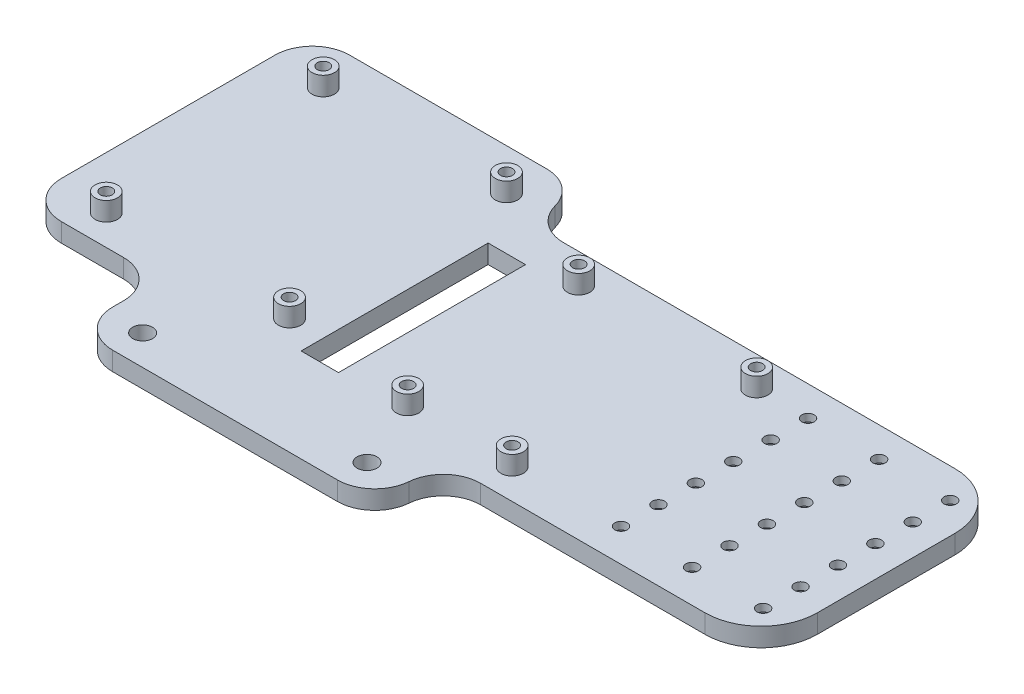
SolidWorks part; units mm, degrees
ref_plane "Front Plane" through (0, 0, 0) normal (0, 0, 1) x (1, 0, 0)
ref_plane "Top Plane" through (0, 0, 0) normal (0, 1, 0) x (1, 0, 0)
ref_plane "Right Plane" through (0, 0, 0) normal (1, 0, 0) x (0, 0, -1)
sketch "Sketch1" plane through (0, 0, 0) normal (0, 1, 0) x (1, 0, 0)
  line L1 (0, 0) -> (270, 0)
  line L2 (0, 0) -> (0, 100)
  line L3 (0, 100) -> (270, 100)
  line L4 (270, 0) -> (270, 100)
  dimension "D1" = 270
  dimension "D2" = 100
extrude "Boss-Extrude1" add sketch "Sketch1" along normal blind 5
sketch "Sketch2" plane through (0, 5, 0) normal (0, 1, 0) x (1, 0, 0)
  line L0 (150.83, 92.803) -> (204.83, 92.803)
  line L1 (10.5038, 92.4135) -> (66.5038, 92.4135)
  line L2 (10.5038, 92.4135) -> (10.5038, 7.4135)
  line L3 (10.5038, 7.4135) -> (66.5038, 7.4135)
  line L4 (66.5038, 92.4135) -> (66.5038, 7.4135)
  line L5 (90.8313, 92.4135) -> (144.8313, 92.4135)
  line L6 (90.8313, 92.4135) -> (90.8313, 23.9135)
  line L7 (90.8313, 23.9135) -> (144.8313, 23.9135)
  line L8 (144.8313, 92.4135) -> (144.8313, 23.9135)
  line L9 (150.83, 92.803) -> (150.83, 24.303)
  line L10 (150.83, 24.303) -> (204.83, 24.303)
  line L11 (204.83, 92.803) -> (204.83, 24.303)
  line L12 (210.8288, 93.1925) -> (264.8288, 93.1925)
  line L13 (210.8288, 93.1925) -> (210.8288, 24.6925)
  line L14 (210.8288, 24.6925) -> (264.8288, 24.6925)
  line L15 (264.8288, 93.1925) -> (264.8288, 24.6925)
  dimension "D1" = 85
  dimension "D2" = 56
  dimension "D3" = 54
  dimension "D4" = 68.5
  dimension "D5" = 3
sketch "Sketch3" plane through (0, 5, 0) normal (0, 1, 0) x (1, 0, 0)
  line L0 (14.0038, 88.9135) -> (63.0038, 88.9135)
  line L1 (14.0038, 88.9135) -> (14.0038, 30.9135)
  line L2 (10.5038, 92.4135) -> (66.5038, 92.4135) construction
  line L3 (10.5038, 92.4135) -> (10.5038, 7.4135) construction
  circle A0 centre (14.0038, 88.9135) radius 1.6
  circle A1 centre (63.0038, 88.9135) radius 1.6
  circle A2 centre (63.0038, 30.9135) radius 1.6
  circle A3 centre (14.0038, 30.9135) radius 1.6
  circle A4 centre (14.0038, 88.9135) radius 3
  circle A5 centre (63.0038, 88.9135) radius 3
  circle A6 centre (63.0038, 30.9135) radius 3
  circle A7 centre (14.0038, 30.9135) radius 3
  dimension "D1" = 3.2
  dimension "D2" = 6
  dimension "D3" = 49
  dimension "D4" = 49
  dimension "D5" = 58
  dimension "D6" = 58
  dimension "D7" = 3.5
  dimension "D8" = 3.5
extrude "Boss-Extrude2" add sketch "Sketch3" along normal blind 5
sketch "Sketch4" plane through (0, 5, 0) normal (0, 1, 0) x (1, 0, 0)
  circle A0 centre (14.0038, 88.9135) radius 1.6
  circle A1 centre (63.0038, 88.9135) radius 1.6
  circle A2 centre (63.0038, 30.9135) radius 1.6
  circle A3 centre (14.0038, 30.9135) radius 1.6
  dimension "D1" = 3.2
  dimension "D2" = 3.2
  dimension "D3" = 3.2
  dimension "D4" = 3.2
extrude "Cut-Extrude1" cut sketch "Sketch4" against normal blind 5
sketch "Sketch5" plane through (0, 0, 0) normal (0, -1, 0) x (-1, 0, 0)
  circle A0 centre (-63.0038, 88.9135) radius 3.25
  circle A1 centre (-14.0038, 88.9135) radius 3.25
  circle A2 centre (-14.0038, 30.9135) radius 3.25
  circle A3 centre (-63.0038, 30.9135) radius 3.25
  dimension "D1" = 6.5
  dimension "D2" = 2
  dimension "D3" = 2
extrude "Cut-Extrude2" cut sketch "Sketch5" against normal blind 3.2
sketch "Sketch6" plane through (0, 5, 0) normal (0, 1, 0) x (1, 0, 0)
  line L0 (94.0313, 77.1735) -> (141.6313, 77.1735)
  line L1 (90.8313, 92.4135) -> (144.8313, 92.4135) construction
  line L2 (144.8313, 92.4135) -> (144.8313, 23.9135) construction
  line L3 (90.8313, 92.4135) -> (90.8313, 23.9135) construction
  circle A0 centre (99.1113, 26.3735) radius 1.6
  circle A1 centre (127.0513, 26.3735) radius 1.6
  circle A2 centre (94.0313, 77.1735) radius 1.6
  circle A3 centre (141.6313, 77.1735) radius 1.6
  circle A4 centre (154.0313, 77.1735) radius 1.6
  circle A5 centre (159.1113, 26.3735) radius 1.6
  circle A6 centre (187.0513, 26.3735) radius 1.6
  circle A7 centre (201.6313, 77.1735) radius 1.6
  circle A8 centre (214.0313, 77.1735) radius 1.6
  circle A9 centre (219.1113, 26.3735) radius 1.6
  circle A10 centre (247.0513, 26.3735) radius 1.6
  circle A11 centre (261.6313, 77.1735) radius 1.6
  dimension "D1" = 3.2
  dimension "D2" = 15.24
  dimension "D3" = 50.8
  dimension "D4" = 50.8
  dimension "D5" = 17.78
  dimension "D6" = 66.04
  dimension "D7" = 45.72
  dimension "D8" = 66.04
  dimension "D9" = 3
extrude "Cut-Extrude3" cut sketch "Sketch6" against normal blind 23.2
sketch "Sketch7" plane through (0, 5, 0) normal (0, 1, 0) x (1, 0, 0)
  circle A0 centre (94.0313, 77.1735) radius 3
  circle A1 centre (141.6313, 77.1735) radius 3
  circle A2 centre (127.0513, 26.3735) radius 3
  circle A3 centre (99.1113, 26.3735) radius 3
  circle A4 centre (94.0313, 77.1735) radius 1.6
  circle A5 centre (141.6313, 77.1735) radius 1.6
  circle A6 centre (127.0513, 26.3735) radius 1.6
  circle A7 centre (99.1113, 26.3735) radius 1.6
  dimension "D1" = 6
extrude "Boss-Extrude3" add sketch "Sketch7" along normal blind 5
sketch "Sketch8" plane through (0, 0, 0) normal (0, -1, 0) x (1, 0, 0)
  circle A0 centre (94.0313, -77.1735) radius 3.25
  circle A1 centre (99.1113, -26.3735) radius 3.25
  circle A2 centre (127.0513, -26.3735) radius 3.25
  circle A3 centre (141.6313, -77.1735) radius 3.25
  dimension "D1" = 6.5
extrude "Cut-Extrude4" cut sketch "Sketch8" against normal blind 3.2
pattern_linear "LPattern1" count 3 spacing 60 along (1, 0, 0) of "Cut-Extrude4", "Boss-Extrude3"
sketch "Sketch9" plane through (0, 5, 0) normal (0, 1, 0) x (1, 0, 0)
  line L0 (0, 0) -> (270, 0) construction
  line L1 (72, 75) -> (82, 75)
  line L2 (72, 75) -> (72, 25)
  line L3 (72, 25) -> (82, 25)
  line L4 (82, 75) -> (82, 25)
  line L5 (0, 100) -> (0, 0) construction
  dimension "D1" = 10
  dimension "D2" = 50
  dimension "D3" = 25
  dimension "D4" = 72
extrude "Cut-Extrude5" cut sketch "Sketch9" against normal blind 13.2
sketch "Sketch11" plane through (0, 5, 0) normal (0, 1, 0) x (1, 0, 0)
  line L0 (270, 100) -> (0, 100) construction
  line L1 (146.6313, 100) -> (270, 100)
  line L2 (146.6313, 100) -> (146.6313, 0)
  line L3 (146.6313, 0) -> (270, 0)
  line L4 (270, 100) -> (270, 0)
  circle A0 centre (141.6313, 77.1735) radius 1.6 construction
  dimension "D1" = 5
extrude "Cut-Extrude7" cut sketch "Sketch11" against normal blind 10
sketch "Sketch12" plane through (0, 5, 0) normal (0, 1, 0) x (1, 0, 0)
  line L0 (0, 0) -> (146.6313, 0) construction
  line L1 (146.6313, 100) -> (146.6313, 0) construction
  circle A0 centre (46.6313, 8) radius 2.65
  circle A1 centre (106.6313, 8) radius 2.65
  point P4 (0, 0)
  dimension "D1" = 5.3
  dimension "D2" = 5.3
  dimension "D3" = 8
  dimension "D4" = 8
  dimension "D5" = 60
  dimension "D6" = 40
extrude "Cut-Extrude8" cut sketch "Sketch12" against normal blind 10
sketch "Sketch13" plane through (0, 5, 0) normal (0, 1, 0) x (1, 0, 0)
  line L0 (141.6313, 85.1735) -> (82, 85.1735)
  line L1 (146.6313, 100) -> (146.6313, 0) construction
  line L2 (72, 95.1735) -> (72, 100)
  line L3 (146.6313, 100) -> (0, 100) construction
  line L4 (72, 75) -> (72, 25) construction
  line L5 (116.6313, 0) -> (116.6313, 8.3735)
  line L6 (0, 0) -> (146.6313, 0) construction
  line L7 (126.6313, 18.3735) -> (136.6313, 18.3735)
  line L8 (36.6313, 0) -> (36.6313, 12.9135)
  line L9 (26.6313, 22.9135) -> (10, 22.9135)
  line L10 (0, 100) -> (0, 0) construction
  line L11 (146.6313, 28.3735) -> (146.6313, 80.1735)
  line L12 (36.6313, 0) -> (116.6313, 0)
  line L13 (0, 32.9135) -> (0, 90)
  line L14 (10, 100) -> (72, 100)
  circle A0 centre (94.0313, 77.1735) radius 1.6 construction
  circle A1 centre (106.6313, 8) radius 2.65 construction
  circle A2 centre (127.0513, 26.3735) radius 3 construction
  circle A3 centre (46.6313, 8) radius 2.65 construction
  circle A4 centre (14.0038, 30.9135) radius 3 construction
  arc A5 (82, 85.1735) -> (72, 95.1735) centre (82, 95.1735) cw
  arc A6 (116.6313, 8.3735) -> (126.6313, 18.3735) centre (126.6313, 8.3735) cw
  arc A7 (36.6313, 12.9135) -> (26.6313, 22.9135) centre (26.6313, 12.9135) ccw
  arc A8 (136.6313, 18.3735) -> (146.6313, 28.3735) centre (136.6313, 28.3735) ccw
  arc A9 (10, 22.9135) -> (0, 32.9135) centre (10, 32.9135) cw
  arc A10 (141.6313, 85.1735) -> (146.6313, 80.1735) centre (141.6313, 80.1735) cw
  arc A11 (0, 90) -> (10, 100) centre (10, 90) cw
  point P39 (146.6313, 18.3735)
  point P42 (0, 22.9135)
  point P45 (146.6313, 85.1735)
  point P48 (0, 100)
  line M30 (0, 0) -> (146.6313, 0)
  line M31 (146.6313, 0) -> (146.6313, 100)
  line M32 (146.6313, 100) -> (0, 100)
  line M33 (0, 100) -> (0, 0)
  dimension "D7" = 10
  dimension "D8" = 10
  dimension "D9" = 5
  dimension "D10" = 10
  dimension "D1" = 0
  dimension "D2" = 8
  dimension "D3" = 10
  dimension "D4" = 8
  dimension "D5" = 10
  dimension "D6" = 8
extrude "Cut-Extrude9" cut sketch "Sketch13" against normal blind 10 contours L9 A9 L8 A7 M33 M30 | L0 A10 L2 A5 M31 M32 | A8 L7 A6 L5 M30 M31
fillet "Fillet1" radius 10 3 edges at (36.6313, 2.5, 0) (116.6313, 2.5, 0) (72, 2.5, -100)
fillet "Fillet2" radius 10 1 edges at (0, 2.5, -100)
sketch "Sketch14" plane through (0, 5, 0) normal (0, 1, 0) x (1, 0, 0)
  line L1 (141.6313, 85.1735) -> (211.6313, 85.1735)
  line L2 (141.6313, 85.1735) -> (141.6313, 18.3735)
  line L3 (141.6313, 18.3735) -> (211.6313, 18.3735)
  line L4 (211.6313, 85.1735) -> (211.6313, 18.3735)
  line L5 (126.6313, 18.3735) -> (136.6313, 18.3735) construction
  line L6 (141.6313, 18.3735) -> (136.6313, 18.3735)
  line L7 (136.6313, 18.3735) -> (136.6313, 27.2758)
  line L8 (136.6313, 27.2758) -> (141.6313, 27.2758)
  line L9 (141.6313, 27.2758) -> (141.6313, 18.3735)
  point P7 (139.1313, 27.2758)
  arc M33 (136.6313, 18.3735) -> (146.6313, 28.3735) centre (136.6313, 28.3735) ccw
  line M34 (146.6313, 28.3735) -> (146.6313, 80.1735)
  arc M35 (146.6313, 80.1735) -> (141.6313, 85.1735) centre (141.6313, 80.1735) ccw
  dimension "D1" = 70
  dimension "D2" = 0
  dimension "D3" = 5
  dimension "D4" = 8.9023
  dimension "D5" = 8.9023
extrude "Boss-Extrude4" add sketch "Sketch14" against normal up to surface (5 mm away) contours L4 L1 L2 L3 M35 M34 M33 | L8 L7 L2 M33 up to face at (72.4461, 0, -44.8907)
sketch "Sketch15" plane through (0, 5, 0) normal (0, 1, 0) x (1, 0, 0)
  line L0 (141.6313, 18.3735) -> (136.6313, 18.3735)
  line L1 (136.6313, 18.3735) -> (136.6313, 19.9644)
  line L2 (136.6313, 19.9644) -> (141.6313, 19.9644)
  line L3 (141.6313, 19.9644) -> (141.6313, 18.3735)
extrude "Boss-Extrude5" add sketch "Sketch15" against normal up to surface (5 mm away) up to face at (82.7706, 0, -39.8238)
hole_wizard "Ø3.0mm Dowel Hole2" positions "3DSketch1" profile "Sketch18" hole size "Ø3.0" standard "ANSI Metric" end condition through all
sketch3d "3DSketch1"
  line L0 (211.6313, 5, -85.1735) -> (82, 5, -85.1735) construction
  point P0 (155.3664, 5, -77.1735)
  dimension "D1" = 8
sketch "Sketch18" plane through (155.3664, 5, -77.1735) normal (1, 0, 0) x (0, 0, 1)
  line L0 (0, 0) -> (0, 5)
  line L1 (0, 5) -> (1.65, 5)
  line L2 (1.65, 5) -> (1.65, 0)
  line L5 (1.65, 0) -> (0, 0)
  line L11 (0, -6.35) -> (0, 107.95) construction
  dimension "Thru Hole Dia." = 3.3
  dimension "Thru Hole Depth" = 5
pattern_linear "LPattern2" count 3 spacing 19 along (1, 0, 0) count 6 spacing 10 along (0, 0, 1) of "Ø3.0mm Dowel Hole2"
sketch "Sketch19" plane through (0, 0, 0) normal (0, -1, 0) x (-1, 0, 0)
  line L1 (-191.6054, 80.2235) -> (-195.1273, 80.2235)
  line L2 (-195.1273, 80.2235) -> (-196.8882, 77.1735)
  line L3 (-196.8882, 77.1735) -> (-195.1273, 74.1235)
  line L4 (-195.1273, 74.1235) -> (-191.6054, 74.1235)
  line L5 (-191.6054, 74.1235) -> (-189.8445, 77.1735)
  line L6 (-189.8445, 77.1735) -> (-191.6054, 80.2235)
  circle A0 centre (-193.3664, 77.1735) radius 3.05 construction
  dimension "D1" = 6.1
extrude "Cut-Extrude10" cut sketch "Sketch19" against normal blind 3
pattern_linear "LPattern3" count 3 spacing 19 along (-1, 0, 0) count 6 spacing 10 along (0, 0, 1) of "Cut-Extrude10"
sketch "Sketch20" plane through (0, 0, 0) normal (0, -1, 0) x (-1, 0, 0)
  line L1 (-138.1095, 77.1735) -> (-139.8704, 80.2235)
  line L2 (-139.8704, 80.2235) -> (-143.3922, 80.2235)
  line L3 (-143.3922, 80.2235) -> (-145.1532, 77.1735)
  line L4 (-145.1532, 77.1735) -> (-143.3922, 74.1235)
  line L5 (-143.3922, 74.1235) -> (-139.8704, 74.1235)
  line L6 (-139.8704, 74.1235) -> (-138.1095, 77.1735)
  line L7 (-92.2704, 80.2235) -> (-95.7922, 80.2235)
  line L8 (-95.7922, 80.2235) -> (-97.5532, 77.1735)
  line L9 (-97.5532, 77.1735) -> (-95.7922, 74.1235)
  line L10 (-95.7922, 74.1235) -> (-92.2704, 74.1235)
  line L11 (-92.2704, 74.1235) -> (-90.5095, 77.1735)
  line L12 (-90.5095, 77.1735) -> (-92.2704, 80.2235)
  line L13 (-95.5895, 26.3735) -> (-97.3504, 29.4235)
  line L14 (-97.3504, 29.4235) -> (-100.8722, 29.4235)
  line L15 (-100.8722, 29.4235) -> (-102.6332, 26.3735)
  line L16 (-102.6332, 26.3735) -> (-100.8722, 23.3235)
  line L17 (-100.8722, 23.3235) -> (-97.3504, 23.3235)
  line L18 (-97.3504, 23.3235) -> (-95.5895, 26.3735)
  line L19 (-123.5295, 26.3735) -> (-125.2904, 29.4235)
  line L20 (-125.2904, 29.4235) -> (-128.8122, 29.4235)
  line L21 (-128.8122, 29.4235) -> (-130.5732, 26.3735)
  line L22 (-130.5732, 26.3735) -> (-128.8122, 23.3235)
  line L23 (-128.8122, 23.3235) -> (-125.2904, 23.3235)
  line L24 (-125.2904, 23.3235) -> (-123.5295, 26.3735)
  circle A0 centre (-141.6313, 77.1735) radius 3.05 construction
  circle A1 centre (-94.0313, 77.1735) radius 3.05 construction
  circle A2 centre (-99.1113, 26.3735) radius 3.05 construction
  circle A3 centre (-127.0513, 26.3735) radius 3.05 construction
  dimension "D1" = 6.1
  dimension "D2" = 6.1
  dimension "D3" = 6.1
  dimension "D4" = 6.1
extrude "Cut-Extrude11" cut sketch "Sketch20" against normal blind 3
sketch "Sketch21" plane through (0, 5, 0) normal (0, 1, 0) x (1, 0, 0)
  line L0 (211.6313, 85.1735) -> (211.6313, 18.3735) construction
  line L1 (201.6313, 89.5349) -> (211.6313, 89.5349)
  line L2 (201.6313, 89.5349) -> (201.6313, 16.2061)
  line L3 (201.6313, 16.2061) -> (211.6313, 16.2061)
  line L4 (211.6313, 89.5349) -> (211.6313, 16.2061)
  point P5 (199.0361, 89.5349)
  dimension "D1" = 0
  dimension "D2" = 10
extrude "Cut-Extrude12" cut sketch "Sketch21" against normal through all
fillet "Fillet5" radius 15 2 edges at (201.6313, 2.5, -18.3735) (201.6313, 2.5, -85.1735)
